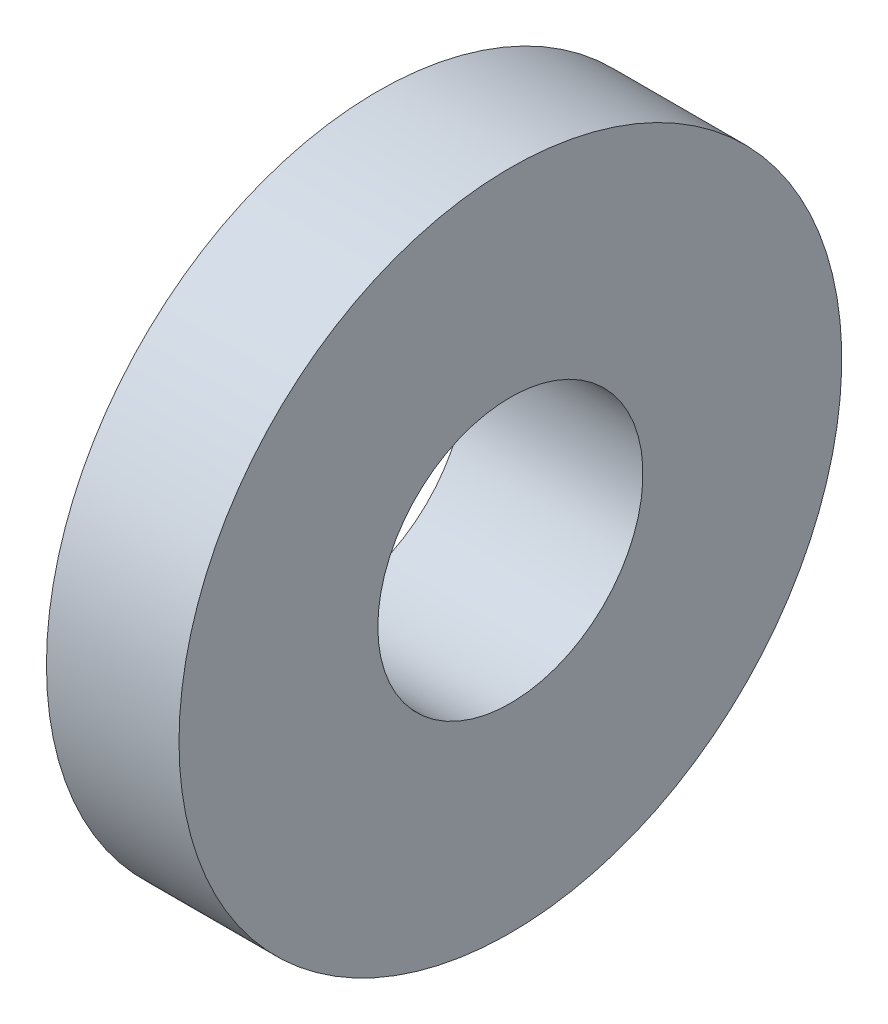
SolidWorks part; units mm, degrees
ref_plane "Front Plane" through (0, 0, 0) normal (0, 0, 1) x (1, 0, 0)
ref_plane "Top Plane" through (0, 0, 0) normal (0, 1, 0) x (1, 0, 0)
ref_plane "Right Plane" through (0, 0, 0) normal (1, 0, 0) x (0, 0, -1)
sketch "Sketch1" plane through (0, 0, 0) normal (0, 0, 1) x (1, 0, 0)
  line L0 (0, 0) -> (0, -2258.0935) construction
  line L1 (0, 0) -> (2258.0935, 0) construction
  line L2 (0, 2.5) -> (0.5, 2.5)
  line L3 (0.5, 2.5) -> (0.5, 3.75)
  line L4 (0.5, 3.75) -> (2, 3.75)
  line L5 (2, 3.75) -> (2, 1.5)
  line L6 (2, 1.5) -> (0, 1.5)
  line L7 (0, 1.5) -> (0, 2.5)
  dimension "D1" = 0.5
  dimension "D2" = 1.5
  dimension "D3" = 3
  dimension "D4" = 5
  dimension "D5" = 7.5
revolve "Revolve1" add sketch "Sketch1" angle 360 about L1
